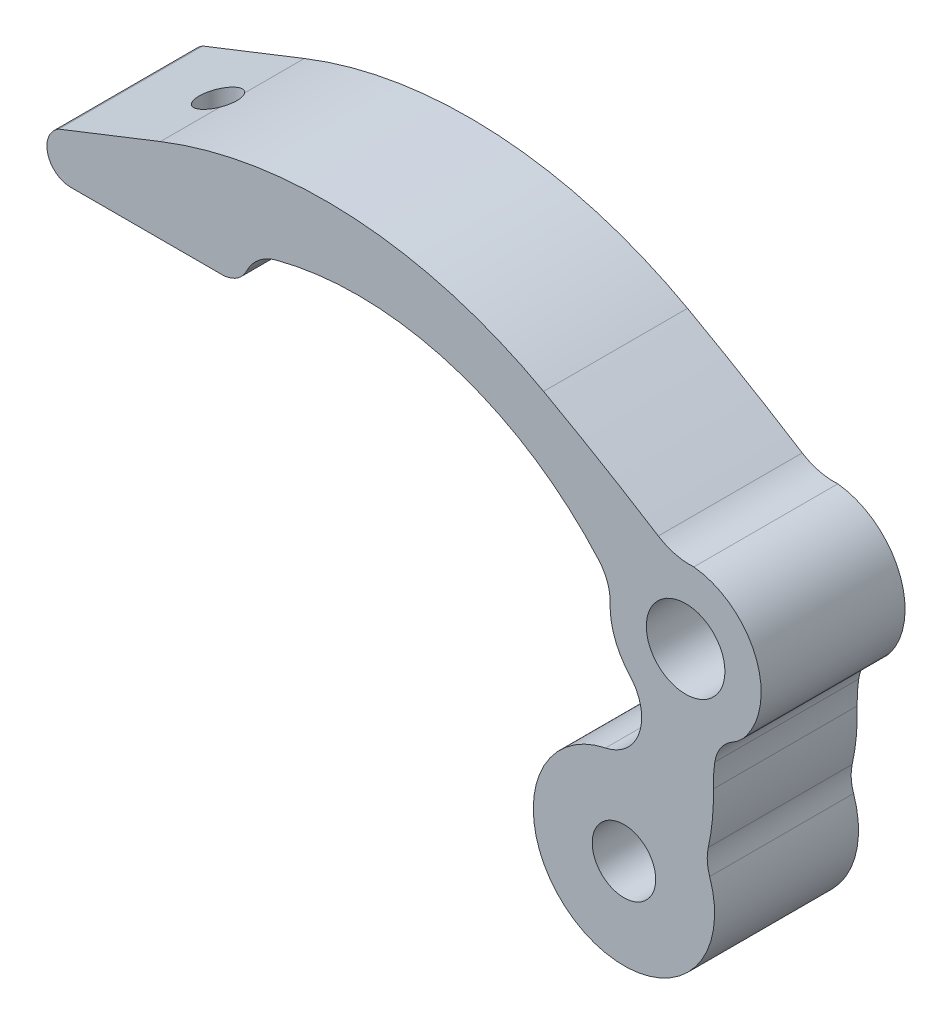
SolidWorks part; units mm, degrees
ref_plane "Front Plane" through (0, 0, 0) normal (0, 0, 1) x (1, 0, 0)
ref_plane "Top Plane" through (0, 0, 0) normal (0, 1, 0) x (1, 0, 0)
ref_plane "Right Plane" through (0, 0, 0) normal (1, 0, 0) x (0, 0, -1)
ref_plane "Plane1" through (0, 0, 0.0762) normal (0, 0, -1) x (-1, 0, 0)
sketch "Sketch1" plane through (0, 0, 0.0762) normal (0, 0, -1) x (-1, 0, 0)
  line L0 (-9.4126, 46.1846) -> (0.5874, 46.1846)
  line L1 (1.3758, 49.127) -> (-5.3512, 51.7766)
  arc A0 (-36.4138, 36.7072) -> (-35.1093, 40.221) centre (-40.1072, 40.0774) ccw
  arc A1 (-35.1093, 40.221) -> (-34.366, 42.2852) centre (-32.1105, 40.3071) cw
  arc A2 (-34.366, 42.2852) -> (-12.9912, 48.806) centre (-18.4165, 28.2967) cw
  arc A3 (-12.9912, 48.806) -> (-11.0596, 47.2158) centre (-13.7584, 45.9058) cw
  arc A4 (-11.0596, 47.2158) -> (-9.4126, 46.1846) centre (-9.4126, 48.0153) ccw
  arc A5 (0.5874, 46.1846) -> (1.3758, 49.127) centre (0.5874, 47.7614) ccw
  arc A6 (-5.3512, 51.7766) -> (-30.7093, 50.1356) centre (-16.2867, 24.0127) ccw
  arc A7 (-30.7093, 50.1356) -> (-38.3004, 45.6433) centre (43.8887, -84.5798) ccw
  arc A8 (-38.3004, 45.6433) -> (-40.6528, 45.0476) centre (-40.3908, 48.9554) cw
  arc A9 (-40.6528, 45.0476) -> (-44.1328, 37.1118) centre (-40.1072, 40.0774) ccw
  arc A10 (-44.1328, 37.1118) -> (-43.2152, 36.2918) centre (-41.7175, 38.8912) ccw
  arc A11 (-43.2152, 36.2918) -> (-42.0402, 34.5584) centre (-44.4113, 34.216) cw
  arc A12 (-42.0402, 34.5584) -> (-41.9371, 32.959) centre (-52.0851, 33.1081) cw
  arc A13 (-41.9371, 32.959) -> (-41.6076, 29.4476) centre (-27.6969, 32.5242) ccw
  arc A14 (-41.6076, 29.4476) -> (-41.6999, 27.8241) centre (-44.5368, 28.7998) cw
  arc A15 (-41.6999, 27.8241) -> (-34.8071, 31.7477) centre (-36.0261, 25.8728) ccw
  arc A16 (-34.8071, 31.7477) -> (-36.4138, 36.7072) centre (-34.1977, 34.6851) cw
extrude "Boss-Extrude1" add sketch "Sketch1" against normal blind 9.525
hole_wizard "Ø5.2 (5.2) Diameter Hole1" positions "Sketch3" profile "Sketch2" hole size "Ø5.2" standard "ANSI Metric"
sketch "Sketch3" plane through (0, 0, 9.6012) normal (0, 0, 1) x (1, 0, 0)
  point P0 (40.1072, 40.0774)
sketch "Sketch2" plane through (40.1072, 40.0774, 9.6012) normal (1, 0, 0) x (0, -1, 0)
  line L0 (0, 0) -> (0, 9.525)
  line L1 (0, 9.525) -> (2.6, 9.525)
  line L2 (2.6, 9.525) -> (2.6, 0)
  line L5 (2.6, 0) -> (0, 0)
  line L11 (0, -6.35) -> (0, 107.95) construction
  dimension "Thru Hole Dia." = 5.2
  dimension "Thru Hole Depth" = 9.525
hole_wizard "Ø4.2 (4.2) Diameter Hole1" positions "Sketch5" profile "Sketch4" hole size "Ø4.2" standard "ANSI Metric"
sketch "Sketch5" plane through (0, 0, 9.6012) normal (0, 0, 1) x (1, 0, 0)
  point P0 (36.0261, 25.8728)
sketch "Sketch4" plane through (36.0261, 25.8728, 9.6012) normal (1, 0, 0) x (0, -1, 0)
  line L0 (0, 0) -> (0, 9.525)
  line L1 (0, 9.525) -> (2.1, 9.525)
  line L2 (2.1, 9.525) -> (2.1, 0)
  line L5 (2.1, 0) -> (0, 0)
  line L11 (0, -6.35) -> (0, 107.95) construction
  dimension "Thru Hole Dia." = 4.2
  dimension "Thru Hole Depth" = 9.525
hole_wizard "Ø2.5 (2.5) Diameter Hole1" positions "Sketch7" profile "Sketch6" hole size "Ø2.5" standard "ANSI Metric"
sketch "Sketch7" plane through (0, 46.1846, 0) normal (0, -1, 0) x (-1, 0, 0)
  point P0 (-4.402, -4.8387)
sketch "Sketch6" plane through (4.402, 46.1846, 4.8387) normal (1, 0, 0) x (0, 0, -1)
  line L0 (0, 0) -> (0, 7.668)
  line L1 (0, 7.668) -> (1.25, 7.668)
  line L2 (1.25, 7.668) -> (1.25, 0)
  line L5 (1.25, 0) -> (0, 0)
  line L11 (0, -6.35) -> (0, 107.95) construction
  dimension "Thru Hole Dia." = 2.5
  dimension "Thru Hole Depth" = 7.668
